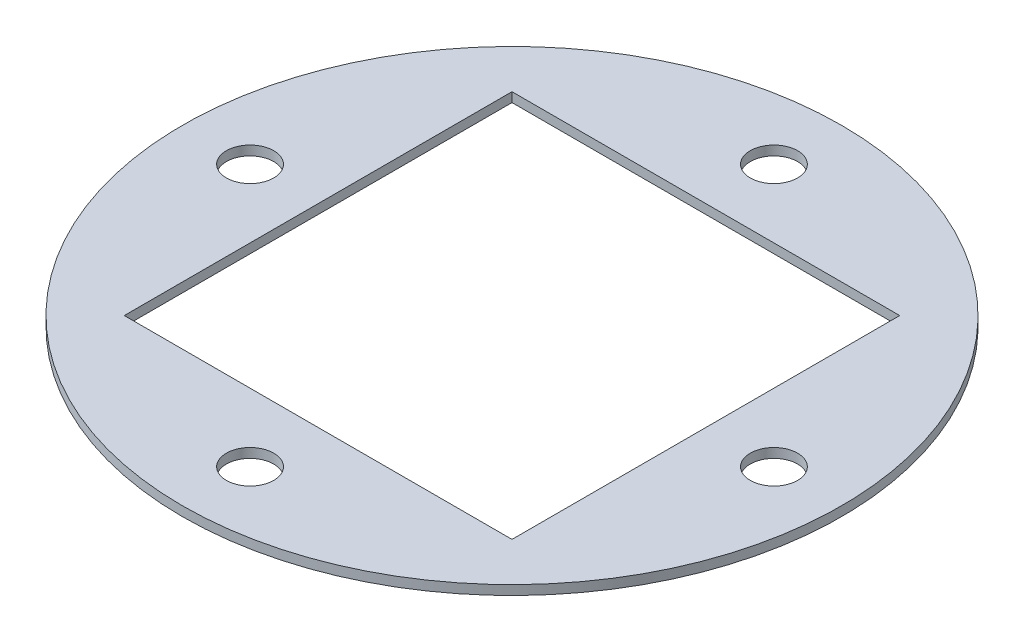
SolidWorks part; units mm, degrees
ref_plane "Front Plane" through (0, 0, 0) normal (0, 0, 1) x (1, 0, 0)
ref_plane "Top Plane" through (0, 0, 0) normal (0, 1, 0) x (1, 0, 0)
ref_plane "Right Plane" through (0, 0, 0) normal (1, 0, 0) x (0, 0, -1)
sketch "Sketch1" plane through (0, 0, 0) normal (0, 1, 0) x (1, 0, 0)
  line L1 (-52.07, 52.07) -> (52.07, 52.07)
  line L2 (-52.07, 52.07) -> (-52.07, -52.07)
  line L3 (-52.07, -52.07) -> (52.07, -52.07)
  line L4 (52.07, 52.07) -> (52.07, -52.07)
  line L5 (-52.07, 52.07) -> (52.07, -52.07) construction
  line L6 (-52.07, -52.07) -> (52.07, 52.07) construction
  circle A0 centre (0, 0) radius 88.519
extrude "Boss-Extrude1" add sketch "Sketch1" along normal blind 2.54
sketch "Sketch2" plane through (0, 2.54, 0) normal (0, 1, 0) x (1, 0, 0)
  circle A0 centre (0, 70.358) radius 6.35
  circle A1 centre (70.358, 0) radius 6.35
  circle A2 centre (0, -70.358) radius 6.35
  circle A3 centre (-70.358, 0) radius 6.35
  point P12 (0, 0)
  dimension "D1" = 70.358
  dimension "D2" = 4
extrude "Cut-Extrude1" cut sketch "Sketch2" against normal through all
